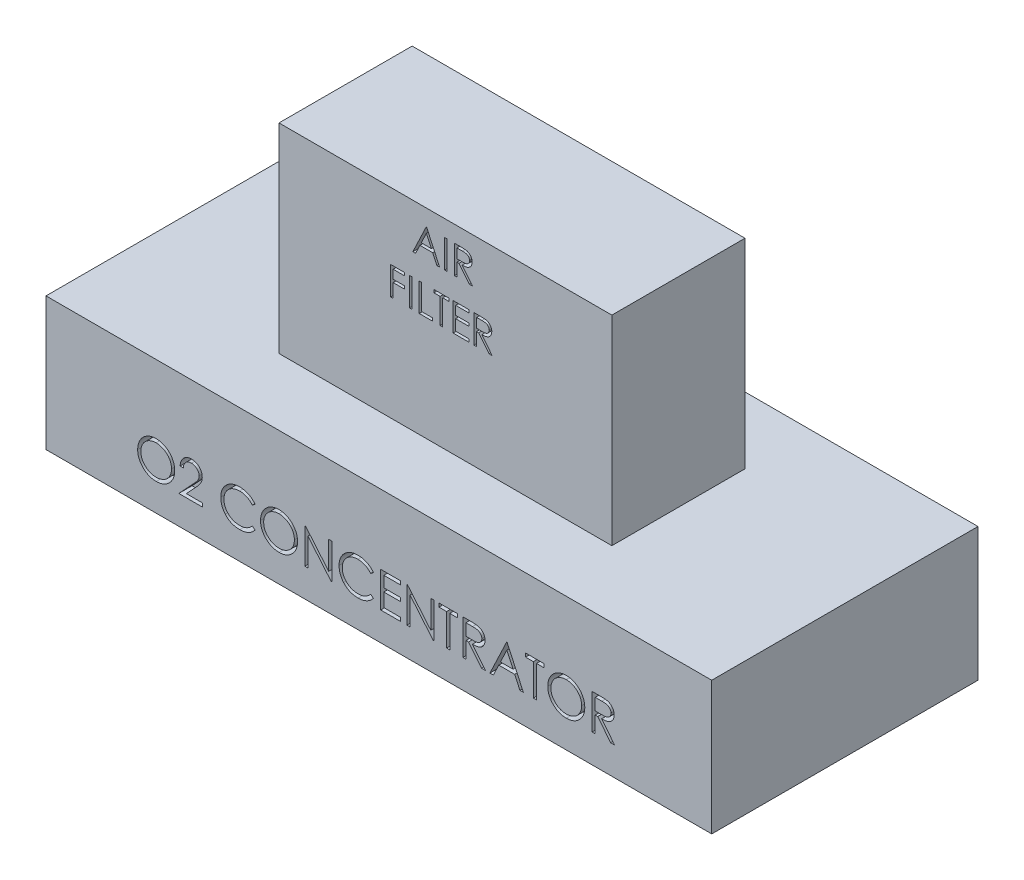
SolidWorks part; units mm, degrees
ref_plane "Front Plane" through (0, 0, 0) normal (0, 0, 1) x (1, 0, 0)
ref_plane "Top Plane" through (0, 0, 0) normal (0, 1, 0) x (1, 0, 0)
ref_plane "Right Plane" through (0, 0, 0) normal (1, 0, 0) x (0, 0, -1)
sketch "Sketch1" plane through (0, 0, 0) normal (0, 0, 1) x (1, 0, 0)
  line L1 (25, -5) -> (-25, -5)
  line L2 (25, -5) -> (25, 5)
  line L3 (25, 5) -> (-25, 5)
  line L4 (-25, -5) -> (-25, 5)
  line L5 (25, -5) -> (-25, 5) construction
  line L6 (25, 5) -> (-25, -5) construction
  point P0 (0, 0)
  dimension "D1" = 10
  dimension "D2" = 50
extrude "Boss-Extrude1" add sketch "Sketch1" along normal mid plane 20
sketch "Sketch2" plane through (0, 0, 10) normal (0, 0, 1) x (1, 0, 0)
  line L0 (-20.1217, -2.8636) -> (19.7126, -2.8636) construction
  text T0 "O2 CONCENTRATOR" font "Century Gothic" height in points 10
extrude "Cut-Extrude1" cut sketch "Sketch2" against normal blind 1
sketch "Sketch3" plane through (0, 5, 0) normal (0, 1, 0) x (1, 0, 0)
  line L1 (12.5, -5) -> (-12.5, -5)
  line L2 (12.5, -5) -> (12.5, 5)
  line L3 (12.5, 5) -> (-12.5, 5)
  line L4 (-12.5, -5) -> (-12.5, 5)
  line L5 (12.5, -5) -> (-12.5, 5) construction
  line L6 (12.5, 5) -> (-12.5, -5) construction
  point P0 (0, 0)
  dimension "D1" = 10
  dimension "D2" = 25
extrude "Boss-Extrude2" add sketch "Sketch3" along normal blind 15
sketch "Sketch4" plane through (0, 0, 5) normal (0, 0, 1) x (1, 0, 0)
  line L0 (-9.281, 16.6506) -> (8.9231, 16.6506) construction
  line L1 (-8.7697, 12.4575) -> (9.4344, 12.4575) construction
  text T0 "AIR" font "Century Gothic" height in points 8
extrude "Cut-Extrude2" cut sketch "Sketch4" against normal blind 1
sketch "Sketch5" plane through (0, 0, 5) normal (0, 0, 1) x (1, 0, 0)
  line L0 (-8.2072, 12.8692) -> (7.4913, 12.8692) construction
  text T0 "FILTER" font "Century Gothic" height in points 8
extrude "Cut-Extrude3" cut sketch "Sketch5" against normal blind 1
